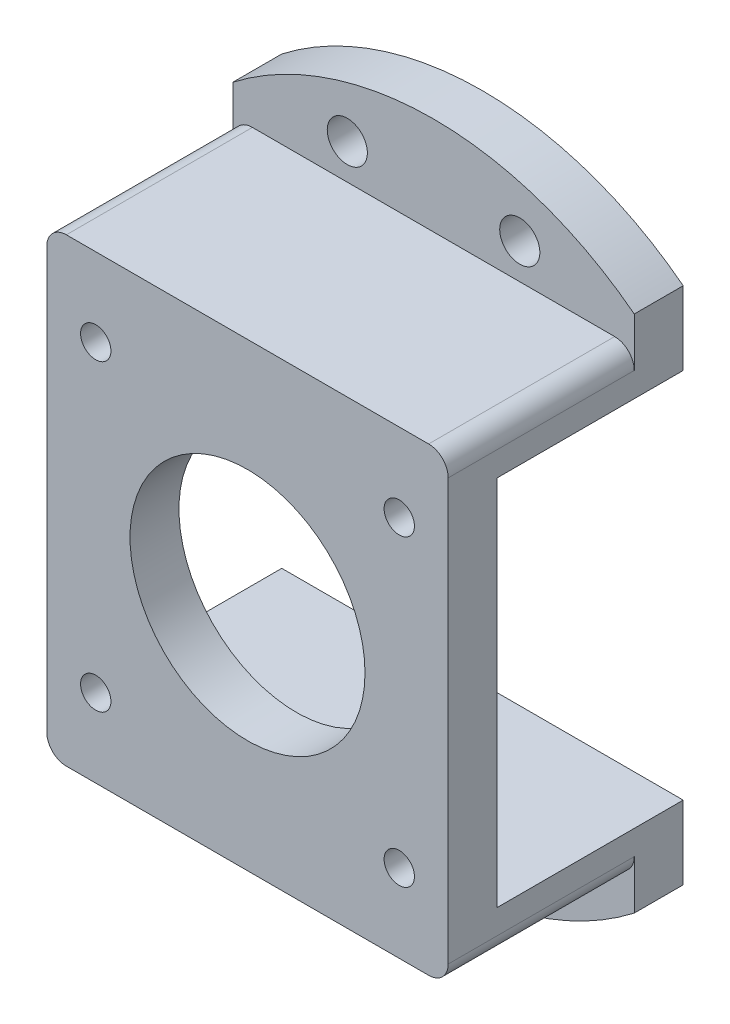
SolidWorks part; units mm, degrees
ref_plane "Front Plane" through (0, 0, 0) normal (0, 0, 1) x (1, 0, 0)
ref_plane "Top Plane" through (0, 0, 0) normal (0, 1, 0) x (1, 0, 0)
ref_plane "Right Plane" through (0, 0, 0) normal (1, 0, 0) x (0, 0, -1)
sketch "Sketch1" plane through (0, 0, 0) normal (0, 0, 1) x (1, 0, 0)
  line L1 (-15.5, -15.5) -> (15.5, -15.5) construction
  line L2 (-15.5, -15.5) -> (-15.5, 15.5) construction
  line L3 (-15.5, 15.5) -> (15.5, 15.5) construction
  line L4 (15.5, -15.5) -> (15.5, 15.5) construction
  line L5 (-15.5, -15.5) -> (15.5, 15.5) construction
  line L6 (-15.5, 15.5) -> (15.5, -15.5) construction
  line L7 (-20.5, -19) -> (20.5, -19)
  line L8 (-20.5, -19) -> (-20.5, 19)
  line L9 (-20.5, 19) -> (20.5, 19)
  line L10 (20.5, -19) -> (20.5, 19)
  line L11 (-20.5, -19) -> (20.5, 19) construction
  line L12 (-20.5, 19) -> (20.5, -19) construction
  circle A0 centre (15.5, 15.5) radius 1.55
  circle A1 centre (-15.5, 15.5) radius 1.55
  circle A2 centre (15.5, -15.5) radius 1.55
  circle A3 centre (-15.5, -15.5) radius 1.55
  circle A4 centre (-15.5, 15.5) radius 2.8 construction
  circle A7 centre (0, 0) radius 12
  point P0 (0, 0)
  point P10 (0, 0)
  dimension "D2" = 3.1
  dimension "D3" = 3.1
  dimension "D4" = 3.1
  dimension "D5" = 3.1
  dimension "D7" = 5.6
  dimension "D8" = 38
  dimension "D9" = 24
  dimension "D1" = 31
  dimension "D6" = 41
extrude "Boss-Extrude1" add sketch "Sketch1" along normal blind 5 contours L7 L10 L9 L8 A4 A3 A2 A0
sketch "Sketch2" plane through (0, 0, 5) normal (0, 0, 1) x (1, 0, 0)
  line L8 (20.5, -19) -> (20.5, 19) construction
  line L9 (-20.5, 19) -> (20.5, 19)
  line L10 (-20.5, 19) -> (-20.5, 23.5)
  line L11 (-20.5, 23.5) -> (20.5, 23.5)
  line L12 (20.5, 19) -> (20.5, 23.5)
  line L13 (-20.5, 19) -> (20.5, 23.5) construction
  line L14 (-20.5, 23.5) -> (20.5, 19) construction
  line L15 (-20.5, 19) -> (20.5, 19) construction
  line L17 (-20.5, -19) -> (20.5, -19)
  line L18 (-20.5, -19) -> (-20.5, -23.5)
  line L19 (-20.5, -23.5) -> (20.5, -23.5)
  line L20 (20.5, -19) -> (20.5, -23.5)
  line L21 (-20.5, -19) -> (20.5, -23.5) construction
  line L22 (-20.5, -23.5) -> (20.5, -19) construction
  point P5 (0, 21.25)
  point P16 (0, -21.25)
  dimension "D1" = 4.5
  dimension "D2" = 4.5
extrude "Boss-Extrude2" add sketch "Sketch2" against normal blind 24
sketch "Sketch3" plane through (0, 0, -19) normal (0, 0, -1) x (-1, 0, 0)
  line L0 (0, 0) -> (0, 28.5) construction
  line L1 (-20.5, 23.5) -> (20.5, 23.5)
  line L2 (-20.5, 23.5) -> (-20.5, 33.5)
  line L3 (-20.5, 33.5) -> (20.5, 33.5)
  line L4 (20.5, 23.5) -> (20.5, 33.5)
  line L5 (-20.5, 23.5) -> (20.5, 33.5) construction
  line L6 (-20.5, 33.5) -> (20.5, 23.5) construction
  line L11 (0, 0) -> (8.807, 27.1051) construction
  line L12 (0, 0) -> (20.5, 0) construction
  line L13 (20.5, -19) -> (20.5, 19) construction
  line L15 (-20.5, -23.5) -> (20.5, -23.5)
  line L16 (-20.5, -23.5) -> (-20.5, -33.5)
  line L17 (-20.5, -33.5) -> (20.5, -33.5)
  line L18 (20.5, -23.5) -> (20.5, -33.5)
  line L19 (-20.5, -23.5) -> (20.5, -33.5) construction
  line L20 (-20.5, -33.5) -> (20.5, -23.5) construction
  circle A2 centre (0, 0) radius 28.5 construction
  circle A3 centre (8.807, 27.1051) radius 2.05
  circle A4 centre (-8.807, 27.1051) radius 2.05
  circle A5 centre (8.807, -27.1051) radius 2.05
  circle A6 centre (-8.807, -27.1051) radius 2.05
  circle A7 centre (0, 0) radius 33.5
  point P5 (0, 28.5)
  point P27 (0, -28.5)
  line M15 (-20.5, -23.5) -> (20.5, -23.5)
  dimension "D1" = 10
  dimension "D2" = 41
  dimension "D4" = 18
  dimension "D3" = 57
  dimension "D5" = 4.1
  dimension "D6" = 10
  dimension "D7" = 41
extrude "Boss-Extrude3" add sketch "Sketch3" against normal blind 5 contours L4 A7 L2 L1 A3 A4 | L16 A7 L18 A6 A5 M15
fillet "Fillet1" radius 2 4 edges at (-20.5, -23.5, -4.5) (20.5, -23.5, -4.5) (-20.5, 23.5, -4.5) (20.5, 23.5, -4.5)
